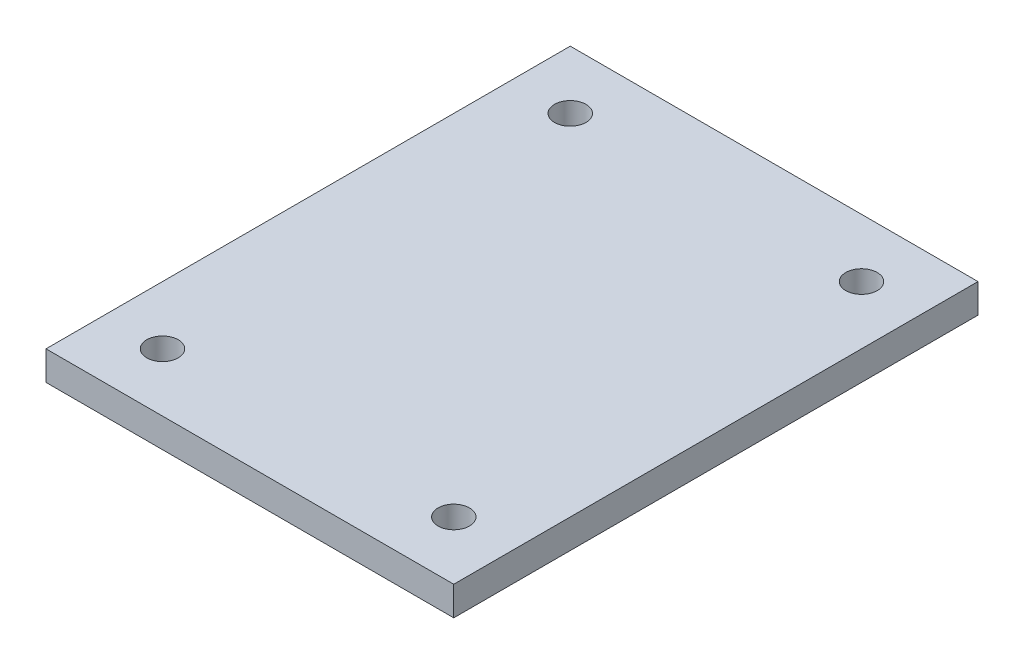
SolidWorks part; units mm, degrees
material "6061 Alloy"
ref_plane "Front Plane" through (0, 0, 0) normal (0, 0, 1) x (1, 0, 0)
ref_plane "Top Plane" through (0, 0, 0) normal (0, 1, 0) x (1, 0, 0)
ref_plane "Right Plane" through (0, 0, 0) normal (1, 0, 0) x (0, 0, -1)
sketch "Sketch1" plane through (0, 0, 0) normal (0, 1, 0) x (1, 0, 0)
  line L1 (-44.45, 57.15) -> (44.45, 57.15)
  line L2 (-44.45, 57.15) -> (-44.45, -57.15)
  line L3 (-44.45, -57.15) -> (44.45, -57.15)
  line L4 (44.45, 57.15) -> (44.45, -57.15)
  line L5 (-44.45, 57.15) -> (44.45, -57.15) construction
  line L6 (-44.45, -57.15) -> (44.45, 57.15) construction
  point P0 (0, 0)
  dimension "D1" = 114.3
  dimension "D2" = 88.9
extrude "Boss-Extrude1" add sketch "Sketch1" along normal blind 6.35
sketch "Sketch3" plane through (0, 0, 0) normal (0, -1, 0) x (1, 0, 0)
  line L0 (0, 0) -> (0, -20.7585) construction
  line L1 (0, 0) -> (-13.1006, 0) construction
  line L2 (-44.45, -57.15) -> (-44.45, 57.15) construction
  line L3 (-44.45, 57.15) -> (44.45, 57.15) construction
  line L4 (44.45, -57.15) -> (-44.45, -57.15) construction
  circle A0 centre (-31.75, 44.45) radius 3.429
  circle A1 centre (-31.75, -44.45) radius 3.429
  circle A2 centre (31.75, 44.45) radius 3.429
  circle A3 centre (31.75, -44.45) radius 3.429
  dimension "D1" = 12.7
  dimension "D2" = 12.7
  dimension "D3" = 12.7
extrude "Cut-Extrude2" cut sketch "Sketch3" against normal up to next
